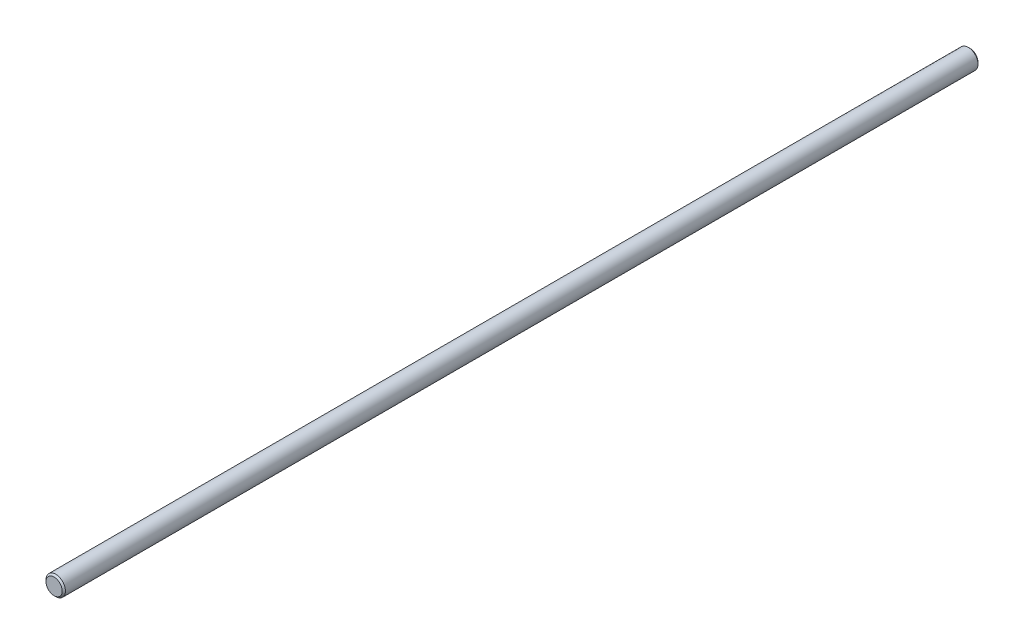
SolidWorks part; units mm, degrees
ref_plane "Front Plane" through (0, 0, 0) normal (0, 0, 1) x (1, 0, 0)
ref_plane "Top Plane" through (0, 0, 0) normal (0, 1, 0) x (1, 0, 0)
ref_plane "Right Plane" through (0, 0, 0) normal (1, 0, 0) x (0, 0, -1)
sketch "Sketch1" plane through (0, 0, 0) normal (0, 0, 1) x (1, 0, 0)
  circle A0 centre (0, 0) radius 3
  dimension "D1" = 6
extrude "Boss-Extrude1" add sketch "Sketch1" against normal blind 282.5
chamfer "Chamfer1" distance 0.5 angle 45 2 edges at (3, 0, -282.5) (3, 0, 0)
